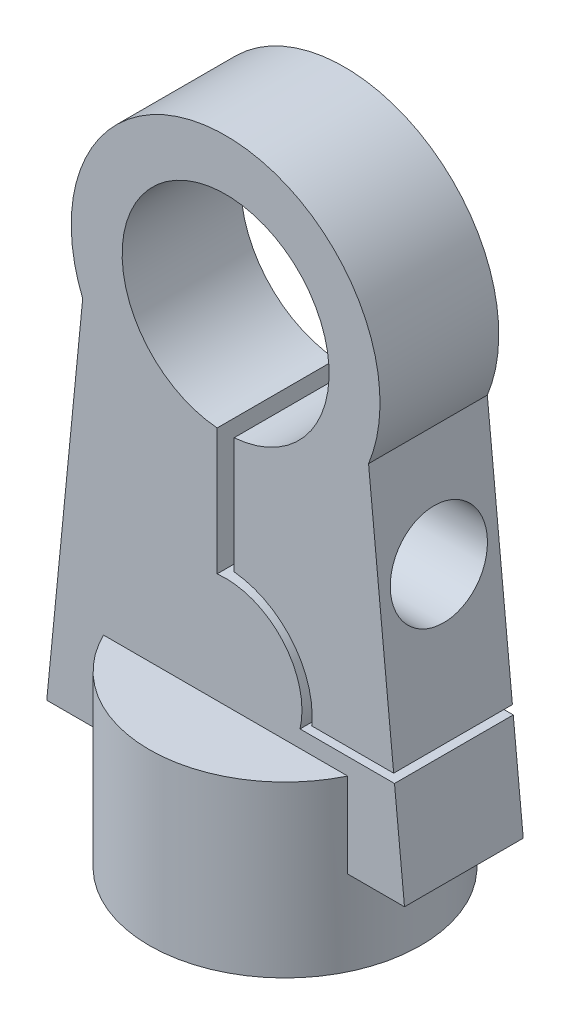
SolidWorks part; units mm, degrees
ref_plane "Front Plane" through (0, 0, 0) normal (0, 0, 1) x (1, 0, 0)
ref_plane "Top Plane" through (0, 0, 0) normal (0, 1, 0) x (1, 0, 0)
ref_plane "Right Plane" through (0, 0, 0) normal (1, 0, 0) x (0, 0, -1)
sketch "Sketch1" plane through (0, 0, 0) normal (0, 0, 1) x (1, 0, 0)
  line L0 (-13, -50) -> (13, -50)
  line L1 (-13, -50) -> (-8.4243, -3.441)
  line L2 (13, -50) -> (8.4243, -3.441)
  arc A0 (-8.4243, -3.441) -> (8.4243, -3.441) centre (0, 0) cw
  circle A1 centre (0, 0) radius 6.1
  dimension "D1" = 12.2
  dimension "D3" = 9.1
  dimension "D2" = 26
  dimension "D5" = 50
extrude "Thickness" add sketch "Sketch1" along normal mid plane 7
sketch "Sketch2" plane through (0, -50, 0) normal (0, -1, 0) x (1, 0, 0)
  line L0 (44.2539, 0) -> (-44.2539, 0) construction
  line L4 (-10.7909, 0) -> (-9.1454, -2.85)
  line L5 (-9.1454, -2.85) -> (-5.8546, -2.85)
  line L6 (-5.8546, -2.85) -> (-4.2091, 0)
  line L14 (4.2091, 0) -> (5.8546, -2.85)
  line L15 (5.8546, -2.85) -> (9.1454, -2.85)
  line L16 (9.1454, -2.85) -> (10.7909, 0)
  line L17 (0, -44.7868) -> (0, 44.7868) construction
  line L18 (4.2091, 0) -> (4.2091, 2.85)
  line L19 (4.2091, 2.85) -> (10.7909, 2.85)
  line L20 (10.7909, 2.85) -> (10.7909, 0)
  line L21 (-10.7909, 0) -> (-10.7909, 2.85)
  line L22 (-10.7909, 2.85) -> (-4.2091, 2.85)
  line L23 (-4.2091, 2.85) -> (-4.2091, 0)
  circle A0 centre (-7.5, 0) radius 2.85
  circle A1 centre (7.5, 0) radius 2.85
  dimension "D2" = 7.5
  dimension "D1" = 5.7
  dimension "D3" = 15
extrude "BotNutCut" cut sketch "Sketch2" against normal blind 2.6 from offset 2 contours A0 | A0 L22 L21 L4 | A0 L6 L23 L22 | A0 L5 L6 | A0 L4 L5 | A1 L14 L15 | A1 L15 L16 | A1 L16 L20 L19 | A1 L19 L18 L14 | A1 offset against normal yes
sketch "Sketch3" plane through (0, -50, 0) normal (0, -1, 0) x (1, 0, 0)
  line L0 (44.2539, 0) -> (-44.2539, 0) construction
  line L1 (0, -44.7868) -> (0, 44.7868) construction
  circle A0 centre (-7.5, 0) radius 1.55
  circle A1 centre (7.5, 0) radius 1.55
  dimension "D3" = 3.1
  dimension "D1" = 15
  dimension "D2" = 7.5
extrude "BotScrewCut" cut sketch "Sketch3" against normal blind 2
sketch "Sketch5" plane through (0, 0, 3.5) normal (0, 0, 1) x (1, 0, 0)
  line L0 (-0.5, -6.0795) -> (-0.5, -14)
  line L1 (-0.5, -14) -> (0.5, -14)
  line L2 (0.5, -14) -> (0.5, -6.0795)
  line L3 (0, -44.7868) -> (0, 44.7868) construction
  line L6 (55, 0) -> (-55, 0) construction
  circle A0 centre (0, 0) radius 6.1 construction
  circle A1 centre (0, -18) radius 5.1
  circle M9 centre (0, 0) radius 6.1
  dimension "D5" = 10.2
  dimension "D1" = 1
  dimension "D2" = 0.5
  dimension "D3" = 18
  dimension "D4" = 14
extrude "Cut-Extrude1" cut sketch "Sketch5" against normal up to surface (7 mm away) contours A1 L2 L0 M9
sketch "Sketch6" plane through (-0.5, 0, 0) normal (1, 0, 0) x (0, 0, -1)
  line L0 (0, 44.2539) -> (0, -44.2539) construction
  line L4 (0, -13.2909) -> (2.85, -11.6454)
  line L5 (2.85, -11.6454) -> (2.85, -8.3546)
  line L6 (2.85, -8.3546) -> (0, -6.7091)
  line L8 (0, -6.7091) -> (-2.85, -8.3546) [skipped]
  line L9 (-2.85, -8.3546) -> (-2.85, -11.6454) [skipped]
  line L10 (-2.85, -11.6454) -> (0, -13.2909) [skipped]
  line L11 (0, -6.7091) -> (-2.85, -6.7091)
  line L12 (-2.85, -6.7091) -> (-2.85, -13.2909)
  line L13 (-2.85, -13.2909) -> (0, -13.2909)
  line L14 (55, 0) -> (-55, 0) construction
  circle A0 centre (0, -10) radius 2.85 construction
  dimension "D1" = 5.7
  dimension "D2" = 10
extrude "RailNutCut" cut sketch "Sketch6" against normal blind 2.6 from offset 2 offset against normal yes
sketch "Sketch7" plane through (-0.5, 0, 0) normal (1, 0, 0) x (0, 0, -1)
  line L0 (0, 44.2539) -> (0, -44.2539) construction
  line L1 (55, 0) -> (-55, 0) construction
  circle A0 centre (0, -10) radius 1.55
  dimension "D1" = 3.1
  dimension "D2" = 10
extrude "RailScrewCut" cut sketch "Sketch7" against normal blind 2.6 and the other way up to surface other way up to face at (10.7122, -26.7205, 0)
sketch "Sketch8" plane through (0.5, 0, 0) normal (-1, 0, 0) x (0, 0, 1)
  line L0 (0, -44.2539) -> (0, 44.2539) construction
  line L1 (55, 0) -> (-55, 0) construction
  circle A0 centre (0, -10) radius 2.85
  dimension "D2" = 5.7
  dimension "D1" = 10
extrude "RailNutHeadCut" cut sketch "Sketch8" against normal up to surface (6.349 mm away) from offset 2.5 offset against normal yes
sketch "Sketch9" plane through (0, 0, 3.5) normal (0, 0, 1) x (1, 0, 0)
  line L0 (55, 0) -> (-55, 0) construction
  line L1 (4, -18.5) -> (11, -18.5)
  line L2 (4, -18.5) -> (4, -19)
  line L3 (4, -19) -> (11, -19)
  line L4 (11, -18.5) -> (11, -19)
  line L5 (0, -44.7868) -> (0, 44.7868) construction
  dimension "D1" = 18.5
  dimension "D2" = 0.5
  dimension "D3" = 7
  dimension "D4" = 4
extrude "MovementCut" cut sketch "Sketch9" against normal up to surface (7 mm away) up to face at (0, -9.001, -3.5)
sketch "Sketch10" plane through (0, 0, 0) normal (0, 0, 1) x (1, 0, 0)
  line L0 (55, 0) -> (-55, 0) construction
  line L2 (0, -44.7868) -> (0, 44.7868) construction
  line L3 (-0.5, -12.9246) -> (-0.5, -13.5279)
  line L4 (5.001, -19) -> (4.3875, -19)
  circle A0 centre (0, -18) radius 4.5
  arc A1 (-0.5, -12.9246) -> (5.001, -19) centre (0, -18) ccw
  arc A3 (-0.5, -12.9246) -> (5.001, -19) centre (0, -18) ccw construction
  dimension "D1" = 9
  dimension "D2" = 18
extrude "Boss-Extrude1" add sketch "Sketch10" along normal mid plane 7 contours L3 A1 L4 A0 | A0
sketch "Sketch11" plane through (0, 0, 0) normal (0, 1, 0) x (1, 0, 0)
  line L0 (-44.2539, 0) -> (44.2539, 0) construction
  line L1 (-20, 12.5) -> (20, 12.5)
  line L2 (-20, 12.5) -> (-20, -12.5)
  line L3 (-20, -12.5) -> (20, -12.5)
  line L4 (20, 12.5) -> (20, -12.5)
  line L5 (0, -44.7868) -> (0, 44.7868) construction
  dimension "D1" = 40
  dimension "D2" = 25
  dimension "D3" = 12.5
  dimension "D4" = 20
extrude "Cut-Extrude2" cut sketch "Sketch11" against normal up to surface (25 mm away) from offset 25 up to face at (-7.5, -50, -1.55) offset against normal yes
ref_plane "Plane1" through (0, -20, 0) normal (0, 1, 0) x (1, 0, 0)
sketch "Sketch12" plane through (0, -20, 0) normal (0, 1, 0) x (1, 0, 0)
  circle A0 centre (0, 0) radius 8
  dimension "D1" = 16
extrude "Boss-Extrude2" add sketch "Sketch12" against normal blind 10
sketch "Sketch13" plane through (0, -20, 0) normal (0, 1, 0) x (1, 0, 0)
  line L0 (-4.792, 0) -> (-4.792, -4.15)
  line L1 (4.792, 0) -> (2.396, 4.15)
  line L2 (2.396, 4.15) -> (-2.396, 4.15)
  line L3 (-2.396, 4.15) -> (-4.792, 0)
  line L5 (-4.792, -4.15) -> (4.792, -4.15)
  line L7 (2.396, -4.15) -> (4.792, 0) [skipped]
  line L8 (-4.792, 0) -> (-2.396, -4.15) [skipped]
  line L10 (4.792, 0) -> (4.792, -4.15)
  line L12 (-44.2539, 0) -> (44.2539, 0) construction
  circle A0 centre (0, 0) radius 4.15 construction
  dimension "D1" = 8.3
extrude "Cut-Extrude3" cut sketch "Sketch13" against normal blind 4.1 from offset 3 offset against normal yes
sketch "Sketch14" plane through (0, -30, 0) normal (0, -1, 0) x (1, 0, 0)
  circle A0 centre (0, 0) radius 2.55
  dimension "D1" = 5.1
extrude "Cut-Extrude4" cut sketch "Sketch14" against normal blind 15
sketch "Sketch15" plane through (0, 0, 0) normal (1, 0, 0) x (0, 0, -1)
  line L0 (0, 44.2539) -> (0, -44.2539) construction
  line L1 (55, -20) -> (-55, -20) construction
  circle A0 centre (0, -19) radius 1.55
  dimension "D1" = 3.1
  dimension "D2" = 1
extrude "Cut-Extrude5" cut sketch "Sketch15" against normal up to surface (9.9534 mm away)
sketch "Sketch16" plane through (0, 0, 0) normal (1, 0, 0) x (0, 0, -1)
  circle A0 centre (0, -19) radius 2.85
  dimension "D1" = 5.7
extrude "Cut-Extrude6" cut sketch "Sketch16" against normal up to surface (2.6534 mm away) from offset 7.3 offset against normal yes
sketch "Sketch17" plane through (0, 0, 0) normal (1, 0, 0) x (0, 0, -1)
  line L0 (0, 44.2539) -> (0, -44.2539) construction
  line L1 (-2.85, -15.7091) -> (-2.85, -22.2909)
  line L3 (0, -22.2909) -> (2.85, -20.6454)
  line L4 (2.85, -20.6454) -> (2.85, -17.3546)
  line L5 (2.85, -17.3546) -> (0, -15.7091)
  line L7 (0, -15.7091) -> (-2.85, -17.3546) [skipped]
  line L8 (-2.85, -20.6454) -> (0, -22.2909) [skipped]
  line L9 (0, -15.7091) -> (-2.85, -15.7091)
  line L10 (0, -22.2909) -> (-2.85, -22.2909)
  circle A0 centre (0, -19) radius 2.85 construction
  point P2 (0, 0)
  point P15 (0, 0)
  point P17 (0, 0)
  point P18 (0, 0)
  dimension "D1" = 5.7
extrude "Cut-Extrude7" cut sketch "Sketch17" against normal blind 2.6 from offset 3
equation "\"Width\"=26"
equation "\"D2@Sketch1\"=\"Width\""
equation "\"fastenWid\"=15"
equation "\"NutDiam\"= 5.7"
equation "\"D1@Sketch3\"=\"fastenWid\""
equation "\"D2@Sketch3\"=\"fastenWid\"/2"
equation "\"ScrewDiam\"=3.1"
equation "\"D3@Sketch3\"=\"ScrewDiam\""
equation "\"ScrewDepth\"=2"
equation "\"D1@BotScrewCut\" = \"ScrewDepth\""
equation "\"D19@BotNutCut\" = \"ScrewDepth\""
equation "\"NutHeight\"=2.6"
equation "\"D1@BotNutCut\" = \"NutHeight\""
equation "\"Thick\"=7"
equation "\"D1@Thickness\" = \"Thick\""
equation "\"RailHeight\"=50"
equation "\"D5@Sketch1\"=\"RailHeight\""
equation "\"RailDiam\"=12.2"
equation "\"D1@Sketch1\"=\"RailDiam\""
equation "\"D3@Sketch1\"=\"RailDiam\"/2 +3"
equation "\"D1@Sketch7\"=\"ScrewDiam\""
equation "\"D1@Sketch2\"=\"NutDiam\""
equation "\"D2@Sketch2\"=\"fastenWid\"/2"
equation "\"D3@Sketch2\"=\"fastenWid\""
equation "\"MovementCut\"=0.5"
equation "\"D2@Sketch9\"=\"MovementCut\""
equation "\"D1@Sketch9\"=\"MovementCut\" +18"
equation "\"D1@Boss-Extrude1\"=\"Thick\""
